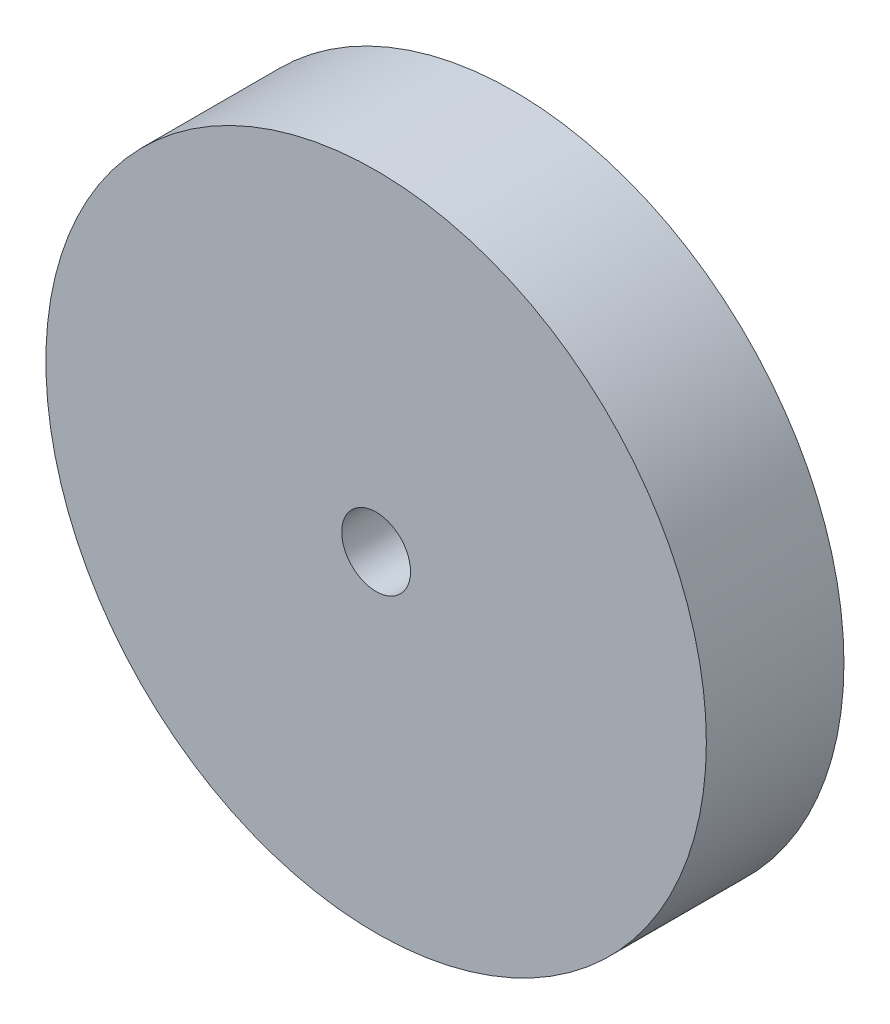
SolidWorks part; units mm, degrees
material "Copper"
ref_plane "Front Plane" through (0, 0, 0) normal (0, 0, 1) x (1, 0, 0)
ref_plane "Top Plane" through (0, 0, 0) normal (0, 1, 0) x (1, 0, 0)
ref_plane "Right Plane" through (0, 0, 0) normal (1, 0, 0) x (0, 0, -1)
sketch "Sketch1" plane through (0, 0, 0) normal (0, 0, 1) x (1, 0, 0)
  circle A0 centre (0, 0) radius 15.24
  circle A1 centre (0, 0) radius 1.5875
  dimension "D1" = 3.175
  dimension "D2" = 30.48
extrude "Boss-Extrude1" add sketch "Sketch1" along normal blind 6.35
